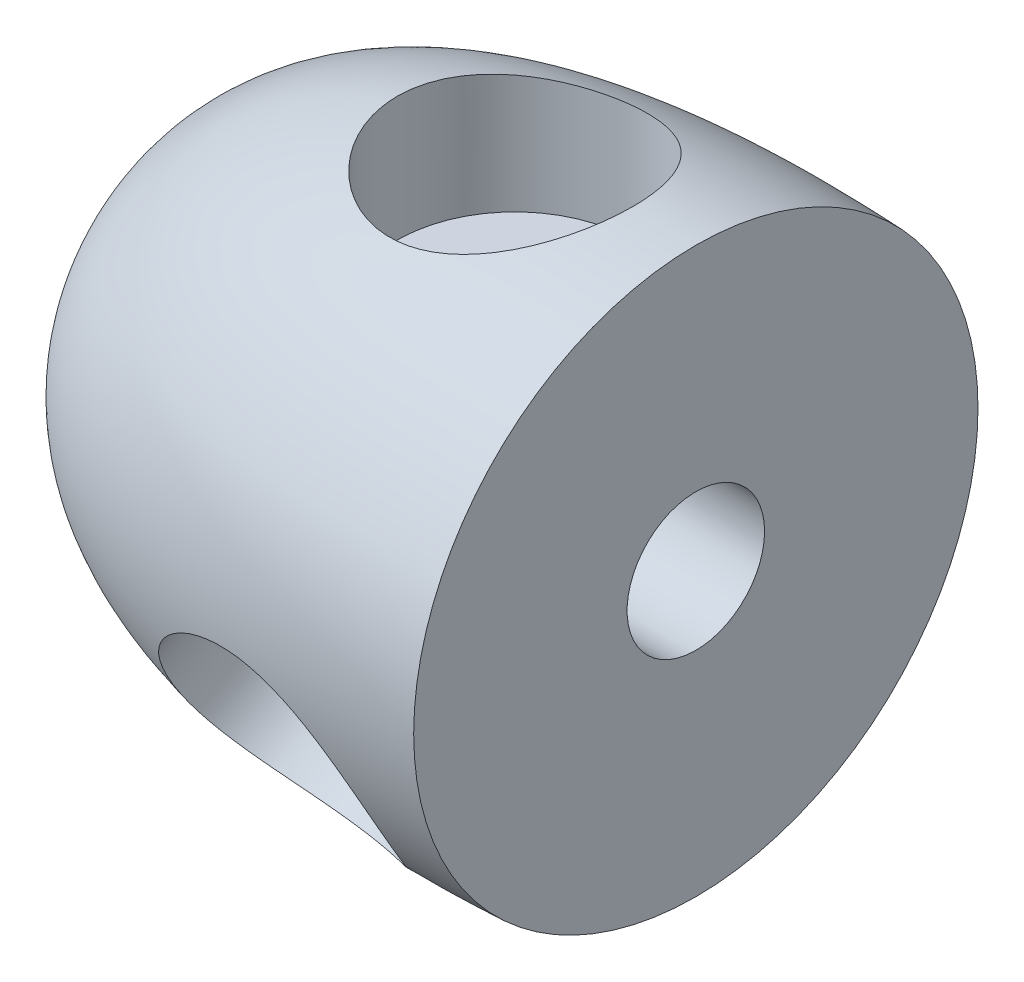
SolidWorks part; units mm, degrees
ref_plane "Front Plane" through (0, 0, 0) normal (0, 0, 1) x (1, 0, 0)
ref_plane "Top Plane" through (0, 0, 0) normal (0, 1, 0) x (1, 0, 0)
ref_plane "Right Plane" through (0, 0, 0) normal (1, 0, 0) x (0, 0, -1)
sketch "Sketch16" plane through (0, 0, 0) normal (0, 0, 1) x (1, 0, 0)
  line L0 (0, 0) -> (38.1, 0)
  line L1 (38.1, 0) -> (38.1, 19.812)
  spline S0 degree 2 poles (0, 0) (0, 21.4716) (38.1, 19.812) knots 0 0 0 1 1 1
revolve "Revolve5" add sketch "Sketch16" angle 360 about L0
sketch "Sketch17" plane through (38.1, 0, 0) normal (1, 0, 0) x (0, 0, -1)
  circle A0 centre (0, 0) radius 4.826
  dimension "D1" = 9.652
extrude "Cut-Extrude3" cut sketch "Sketch17" against normal blind 12.7
ref_plane "Plane4" through (0, 19.812, 0) normal (0, 1, 0) x (1, 0, 0)
sketch "Sketch19" plane through (0, 19.812, 0) normal (0, 1, 0) x (1, 0, 0)
  line L0 (38.1, -19.812) -> (38.1, 19.812) construction
  circle A0 centre (25.4, 0) radius 8.255
  dimension "D1" = 16.51
  dimension "D2" = 12.7
extrude "Cut-Extrude4" cut sketch "Sketch19" against normal mid plane 20.32
pattern_circular "CirPattern1" count 3 over 360 about axis through (0, 0, 0) along (1, 0, 0) of "Cut-Extrude4"
